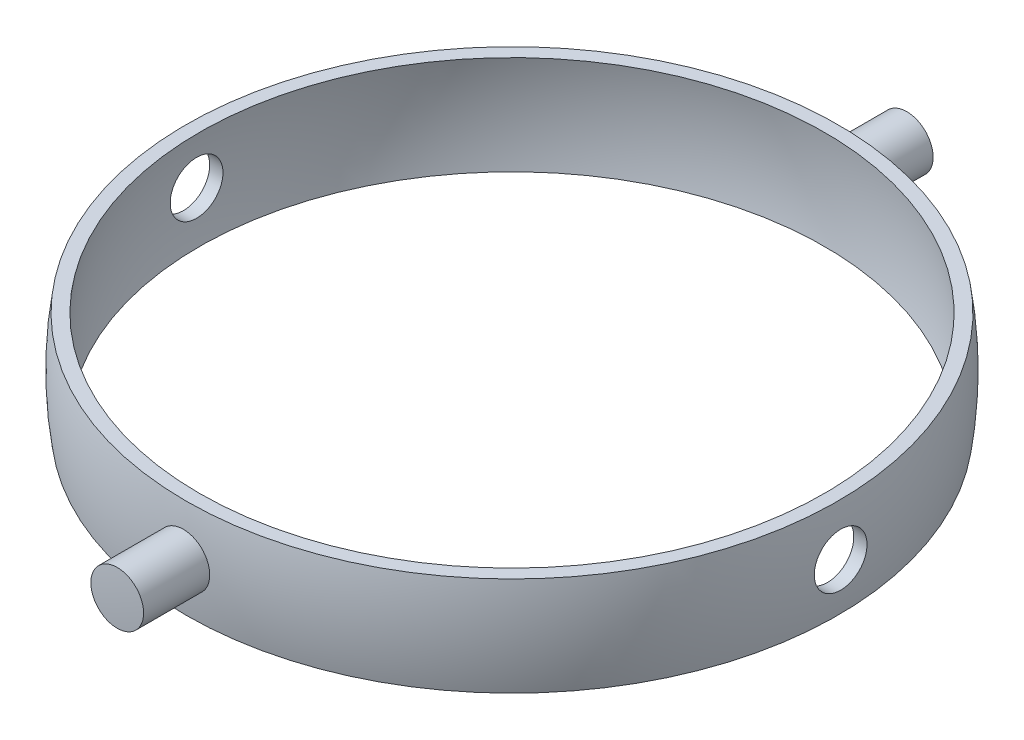
SolidWorks part; units mm, degrees
ref_plane "Front Plane" through (0, 0, 0) normal (0, 0, 1) x (1, 0, 0)
ref_plane "Top Plane" through (0, 0, 0) normal (0, 1, 0) x (1, 0, 0)
ref_plane "Right Plane" through (0, 0, 0) normal (1, 0, 0) x (0, 0, -1)
sketch "Sketch1" plane through (0, 0, 0) normal (0, 0, 1) x (1, 0, 0)
  line L0 (0, 18.4206) -> (0, 0) construction
  line L1 (0, 0) -> (-52.1813, 0) construction
  line L2 (-49.4343, 7.5) -> (-47.4104, 7.5)
  line L3 (-49.4343, -7.5) -> (-47.4104, -7.5)
  arc A0 (-49.4343, 7.5) -> (-49.4343, -7.5) centre (0, 0) ccw
  arc A1 (-47.4104, 7.5) -> (-47.4104, -7.5) centre (0, 0) ccw
  dimension "D1" = 50
  dimension "D2" = 48
  dimension "D3" = 15
revolve "Revolve1" add sketch "Sketch1" angle 360 about L0
sketch "Sketch2" plane through (0, 0, 0) normal (1, 0, 0) x (0, 0, -1)
  circle A0 centre (0, 0) radius 4
  dimension "D1" = 8
extrude "Cut-Extrude1" cut sketch "Sketch2" against normal through all both and the other way through all
ref_plane "Plane1" through (0, 0, 60) normal (0, 0, 1) x (1, 0, 0)
sketch "Sketch3" plane through (0, 0, 60) normal (0, 0, 1) x (1, 0, 0)
  circle A0 centre (0, 0) radius 4
  dimension "D1" = 8
extrude "Boss-Extrude1" add sketch "Sketch3" against normal up to surface (10.1603 mm away)
mirror "Mirror1" about plane through (0, 0, 0) normal (0, 0, 1) of "Boss-Extrude1"
sketch "Sketch4" plane through (0, 0, 0) normal (1, 0, 0) x (0, 0, -1)
  line L0 (0, 43.0244) -> (0, 0) construction
  line L1 (0, 0) -> (-60, 0) construction
  line L2 (-60, 4) -> (-60, -4) construction
  line L3 (0, 70) -> (0, 60)
  line L4 (0, -60) -> (0, -70)
  arc A0 (0, 70) -> (0, -70) centre (0, 0) ccw
  arc A1 (0, 60) -> (0, -60) centre (0, 0) ccw
  point P10 (0, 0)
  point P11 (0, 0)
  point P12 (0, 0)
  dimension "D1" = 70
  dimension "D2" = 60
revolve "Cut-Revolve1" cut sketch "Sketch4" angle 360 about L0
